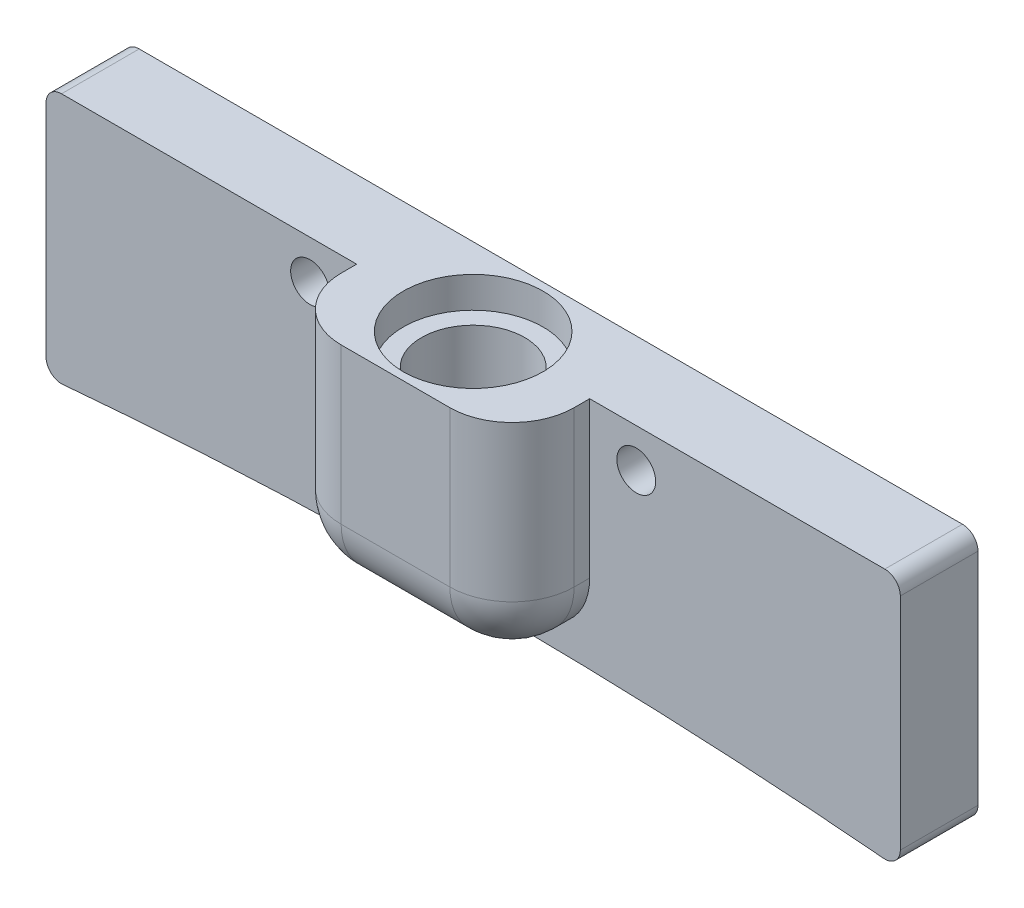
SolidWorks part; units mm, degrees
material "6061 Alloy"
ref_plane "Front Plane" through (0, 0, 0) normal (0, 0, 1) x (1, 0, 0)
ref_plane "Top Plane" through (0, 0, 0) normal (0, 1, 0) x (1, 0, 0)
ref_plane "Right Plane" through (0, 0, 0) normal (1, 0, 0) x (0, 0, -1)
ref_plane "Plane1" through (0, 0, 0) normal (0, 0, -1) x (-1, 0, 0)
sketch "Sketch1" plane through (0, 0, 0) normal (0, 0, -1) x (-1, 0, 0)
  line L0 (27.5, -16.2631) -> (27.5, 0)
  line L1 (27.5, 0) -> (-27.5, 0)
  line L2 (-27.5, 0) -> (-27.5, -16.2631)
  arc A0 (-27.5, -16.2631) -> (27.5, -16.2631) centre (0, -315) cw
extrude "Boss-Extrude1" add sketch "Sketch1" against normal blind 5
sketch "Sketch4" plane through (0, 0, 5) normal (0, 0, 1) x (1, 0, 0)
  line L0 (7.5, 0) -> (7.5, -14)
  line L1 (7.5, -14) -> (-7.5, -14)
  line L2 (-7.5, -14) -> (-7.5, 0)
  line L3 (-7.5, 0) -> (7.5, 0)
extrude "Boss-Extrude2" add sketch "Sketch4" along normal blind 5
hole_wizard "CBORE for M6 Hex Head Bolt1" positions "Sketch6" profile "Sketch5" counterbore size "M6" standard "ANSI Metric"
sketch "Sketch6" plane through (0, 0, 0) normal (0, 1, 0) x (1, 0, 0)
  point P0 (0, -5)
sketch "Sketch5" plane through (0, 0, 5) normal (1, 0, 0) x (0, 0, 1)
  line L0 (0, 0) -> (0, 11.997)
  line L1 (0, 11.997) -> (3.3235, 10)
  line L2 (3.3235, 10) -> (3.3235, 2)
  line L3 (3.3235, 2) -> (4.5, 2)
  line L4 (4.5, 2) -> (4.5, 0)
  line L5 (4.5, 0) -> (0, 0)
  line L10 (0, 11.997) -> (-3.3235, 10) construction
  line L11 (0, -6.35) -> (0, 107.95) construction
  dimension "Hole Dia." = 6.647
  dimension "Hole Depth" = 10
  dimension "C'Bore Dia." = 9
  dimension "C'Bore Depth" = 2
  dimension "Drill Angle" = 118
cosmetic thread "Cosmetic Thread1" parameters "D1"=8, "D2"=8
fillet "Fillet1" radius 1 4 edges at (27.5, 0, 2.5) (-27.5, 0, 2.5) (27.5, -16.2631, 2.5) (-27.5, -16.2631, 2.5)
fillet "Fillet2" radius 4 5 edges at (7.5, -14, 7.5) (7.5, -7, 10) (-7.5, -14, 7.5) (0, -14, 10) (-7.5, -7, 10)
hole_wizard "M3x0.5 Tapped Hole1" positions "3DSketch1" profile "Sketch7" tap size "M3x0.5" standard "ANSI Metric"
sketch3d "3DSketch1"
  line L0 (-7.5, 0, 5) -> (-7.5, -10, 5) construction
  line L1 (7.5, -10, 5) -> (7.5, 0, 5) construction
  line L2 (-26.5, 0, 5) -> (-7.5, 0, 5) construction
  point P0 (-10.5, -2.5, 5)
  point P2 (10.5, -2.5, 5)
  dimension "D1" = 3
  dimension "D2" = 3
  dimension "D3" = 2.5
sketch "Sketch7" plane through (-10.5, -2.5, 5) normal (1, 0, 0) x (0, -1, 0)
  line L0 (0, 0) -> (0, 5.7511)
  line L1 (0, 5.7511) -> (1.25, 5)
  line L2 (1.25, 5) -> (1.25, 0)
  line L5 (1.25, 0) -> (0, 0)
  line L10 (0, 5.7511) -> (-1.25, 5) construction
  line L11 (0, -6.35) -> (0, 107.95) construction
  dimension "Tap Drill Dia." = 2.5
  dimension "Tap Drill Depth" = 5
  dimension "Drill Angle" = 118
